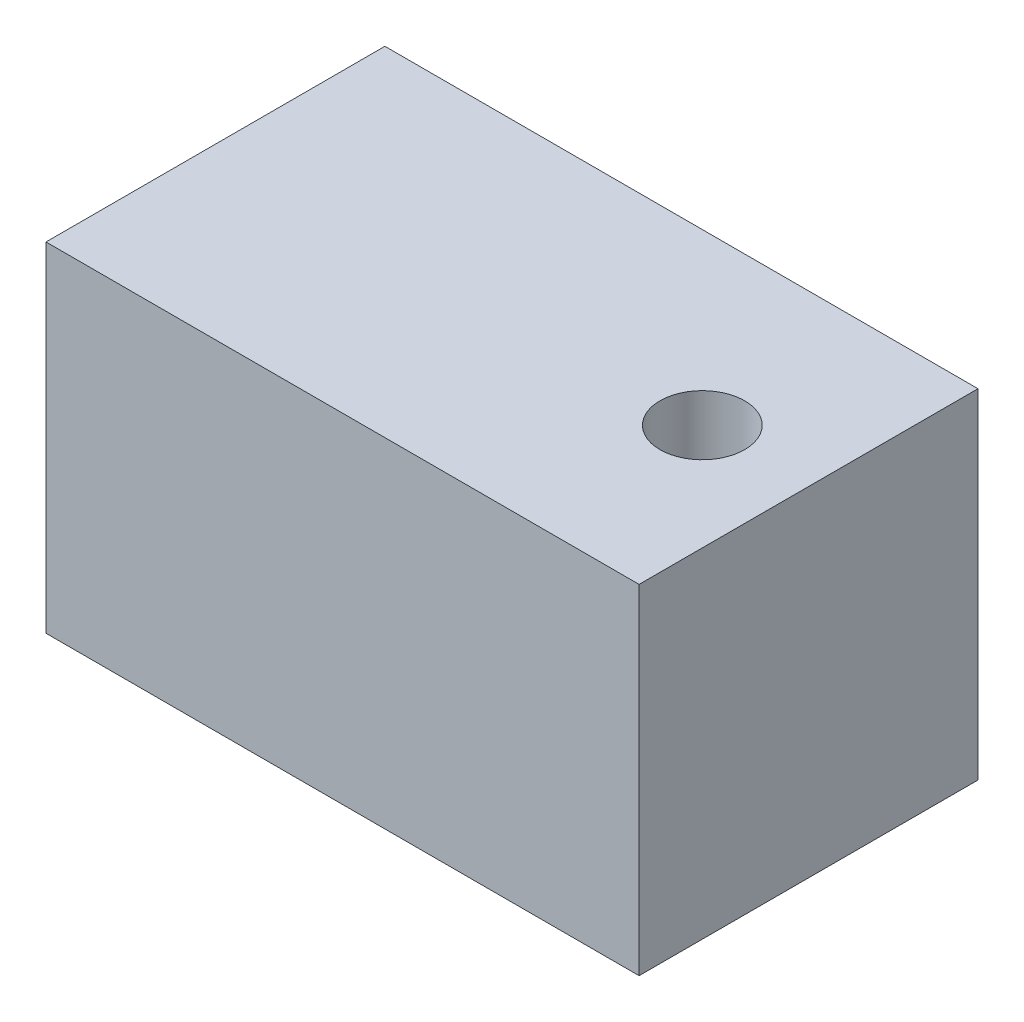
SolidWorks part; units mm, degrees
ref_plane "Front Plane" through (0, 0, 0) normal (0, 0, 1) x (1, 0, 0)
ref_plane "Top Plane" through (0, 0, 0) normal (0, 1, 0) x (1, 0, 0)
ref_plane "Right Plane" through (0, 0, 0) normal (1, 0, 0) x (0, 0, -1)
sketch "Sketch1" plane through (0, 0, 0) normal (0, 1, 0) x (1, 0, 0)
  line L1 (0, 0) -> (44.45, 0)
  line L2 (0, 0) -> (0, 25.4)
  line L3 (0, 25.4) -> (44.45, 25.4)
  line L4 (44.45, 0) -> (44.45, 25.4)
  dimension "D1" = 25.4
  dimension "D2" = 44.45
extrude "Boss-Extrude1" add sketch "Sketch1" along normal blind 25.4
sketch "Sketch2" plane through (0, 25.4, 0) normal (0, 1, 0) x (1, 0, 0)
  line L0 (44.45, 0) -> (44.45, 25.4) construction
  line L1 (0, 25.4) -> (0, 0) construction
  circle A0 centre (36.4884, 12.7) radius 3.175
  point P4 (44.45, 12.7)
  dimension "D1" = 6.35
  dimension "D2" = 36.4884
extrude "Cut-Extrude1" cut sketch "Sketch2" against normal through all
sketch "Sketch3" plane through (0, 0, 0) normal (-1, 0, 0) x (0, 0, 1)
  line L0 (-25.4, 25.4) -> (-25.4, 0) construction
  line L1 (-25.4, 25.4) -> (0, 25.4) construction
  circle A0 centre (-12.7, 12.7) radius 4.7625
  point P4 (-25.4, 12.7)
  point P7 (-12.7, 25.4)
  dimension "D1" = 9.525
hole_wizard "3/8-16 Tapped Hole1" positions "Sketch8" profile "Sketch5" tap size "3/8-16" standard "ANSI Inch"
sketch "Sketch8" plane through (0, 0, 0) normal (-1, 0, 0) x (0, 0, 1)
  point P0 (-12.7, 12.7)
cosmetic thread "Hole Thread1"
sketch "Sketch5" plane through (0, 12.7, -12.7) normal (0, 1, 0) x (0, 0, 1)
  line L0 (0, 0) -> (0, 27.7847)
  line L1 (0, 27.7847) -> (3.9687, 25.4)
  line L2 (3.9687, 25.4) -> (3.9687, 0)
  line L5 (3.9687, 0) -> (0, 0)
  line L10 (0, 27.7847) -> (-3.9688, 25.4) construction
  line L11 (0, -6.35) -> (0, 107.95) construction
  dimension "Tap Drill Dia." = 7.9375
  dimension "Tap Drill Depth" = 25.4
  dimension "Drill Angle" = 118
